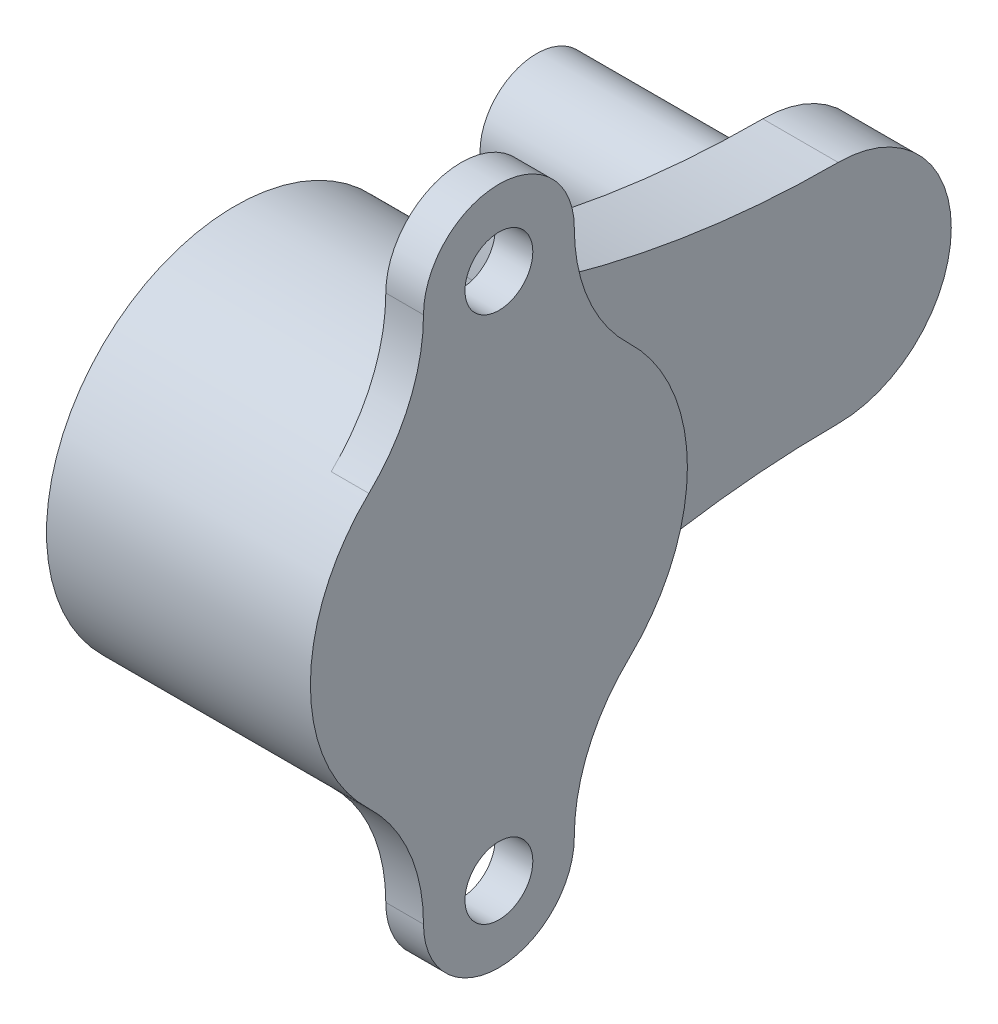
SolidWorks part; units mm, degrees
material "Plain Carbon Steel"
ref_plane "Front Plane" through (0, 0, 0) normal (0, 0, 1) x (1, 0, 0)
ref_plane "Top Plane" through (0, 0, 0) normal (0, 1, 0) x (1, 0, 0)
ref_plane "Right Plane" through (0, 0, 0) normal (1, 0, 0) x (0, 0, -1)
sketch "Sketch1" plane through (0, 0, 0) normal (0, 0, 1) x (1, 0, 0)
  line L3 (15, 25) -> (-15, 25)
  line L6 (-15, 25) -> (-15, 22.5)
  line L8 (15, 5) -> (15, 25)
  line L11 (-15, 5) -> (15, 5)
  line L12 (0, 0) -> (-44.4248, 0) construction
  line L13 (-15, 7.5) -> (-12.5, 7.5)
  line L14 (-12.5, 7.5) -> (-12.5, 22.5)
  line L15 (-12.5, 22.5) -> (-15, 22.5)
  line L16 (-15, 7.5) -> (-15, 5)
  point P1 (0, 0)
  point P4 (0, 0)
  point P7 (0, 0)
  point P8 (0, 0)
  dimension "D2" = 25
  dimension "D3" = 2.5
  dimension "D5" = 30
  dimension "D6" = 15
  dimension "D8" = 5
  dimension "D11" = 2.5
  dimension "D12" = 2.5
revolve "Revolve1" add sketch "Sketch1" angle 360 about L12
fillet "Fillet1" radius 1 1 edges at (-15, 0, -7.5)
sketch "Sketch2" plane through (15, 0, 0) normal (1, 0, 0) x (0, 0, -1)
  circle A2 centre (0, 35) radius 4.5
  circle A3 centre (0, -35) radius 4.5
  circle A10 centre (0, 0) radius 35 construction
  arc A11 (10, 35) -> (-10, 35) centre (0, 35) ccw
  arc A12 (-10, -35) -> (10, -35) centre (0, -35) ccw
  arc A13 (-10, 35) -> (-17.2414, 18.1034) centre (-33.3333, 35) cw
  circle A14 centre (0, 0) radius 25 construction
  arc A15 (-17.2414, 18.1034) -> (-17.2414, -18.1034) centre (0, 0) ccw
  arc A16 (10, 35) -> (17.2414, 18.1034) centre (33.3333, 35) ccw
  arc A17 (-10, -35) -> (-17.2414, -18.1034) centre (-33.3333, -35) ccw
  arc A18 (10, -35) -> (17.2414, -18.1034) centre (33.3333, -35) cw
  arc A19 (17.2414, -18.1034) -> (17.2414, 18.1034) centre (0, 0) ccw
  point P25 (0, 0)
  point P26 (0, 0)
  dimension "D4" = 9
  dimension "D1" = 70
  dimension "D2" = 20
extrude "Boss-Extrude2" add sketch "Sketch2" along normal blind 5
sketch "Sketch3" plane through (0, 0, 0) normal (1, 0, 0) x (0, 0, -1)
  line L0 (8.8, 23.4) -> (8.8, -23.4)
  arc A0 (55, -15) -> (55, 15) centre (55, 0) ccw
  arc A1 (55, 15) -> (8.8, 23.4) centre (55, 146.25) cw
  circle A2 centre (0, 0) radius 25 construction
  arc A3 (55, -15) -> (8.8, -23.4) centre (55, -146.25) ccw
  arc A4 (17.2414, 18.1034) -> (-17.2414, 18.1034) centre (0, 0) ccw construction
  arc A5 (-17.2414, -18.1034) -> (17.2414, -18.1034) centre (0, 0) ccw construction
  dimension "D1" = 30
  dimension "D2" = 55
extrude "Boss-Extrude3" add sketch "Sketch3" along normal blind 10
sketch "Sketch4" plane through (0, 0, 0) normal (-1, 0, 0) x (0, 0, 1)
  circle A0 centre (-55, 0) radius 7.5
  dimension "D1" = 15
extrude "Boss-Extrude4" add sketch "Sketch4" along normal blind 30
